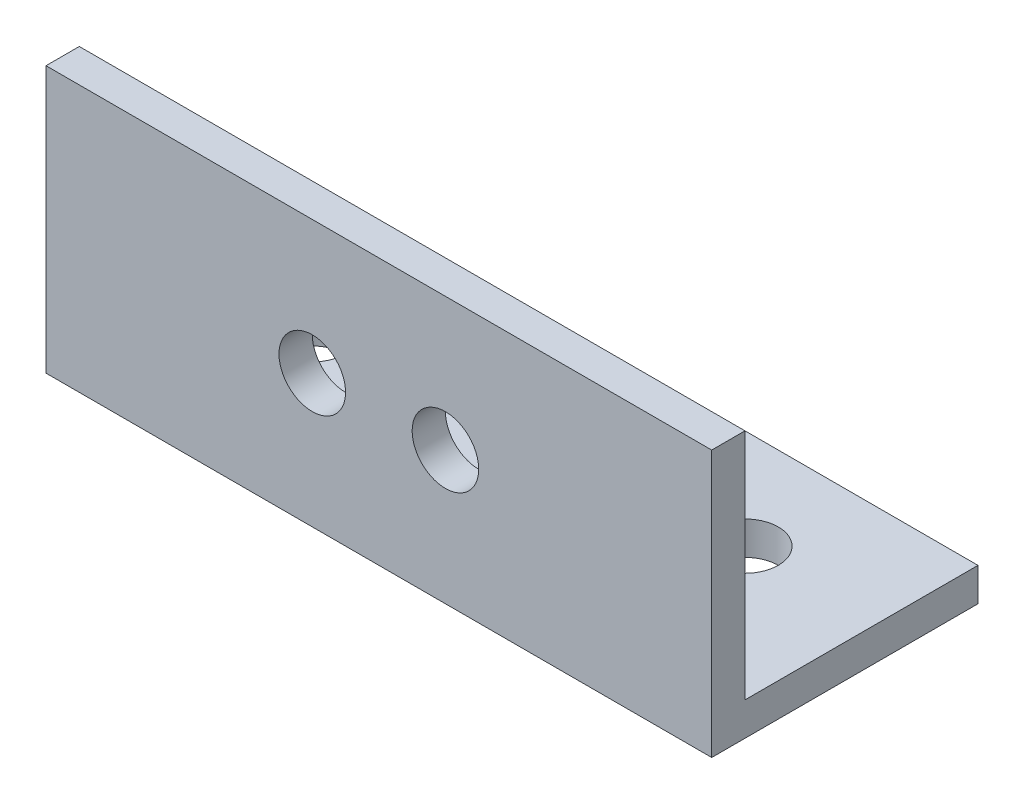
SolidWorks part; units mm, degrees
material "6061-T6 (SS)"
ref_plane "Front Plane" through (0, 0, 0) normal (0, 0, 1) x (1, 0, 0)
ref_plane "Top Plane" through (0, 0, 0) normal (0, 1, 0) x (1, 0, 0)
ref_plane "Right Plane" through (0, 0, 0) normal (1, 0, 0) x (0, 0, -1)
sketch "Sketch1" plane through (0, 0, 0) normal (0, 1, 0) x (1, 0, 0)
  line L1 (-31.75, 12.7) -> (31.75, 12.7)
  line L2 (-31.75, 12.7) -> (-31.75, -12.7)
  line L3 (-31.75, -12.7) -> (31.75, -12.7)
  line L4 (31.75, 12.7) -> (31.75, -12.7)
  line L5 (-31.75, 12.7) -> (31.75, -12.7) construction
  line L6 (-31.75, -12.7) -> (31.75, 12.7) construction
  point P0 (0, 0)
  dimension "D1" = 63.5
  dimension "D2" = 25.4
extrude "Boss-Extrude1" add sketch "Sketch1" along normal blind 3.175
sketch "Sketch2" plane through (0, 3.175, 0) normal (0, 1, 0) x (1, 0, 0)
  line L0 (31.75, -12.7) -> (31.75, 12.7) construction
  line L1 (-31.75, -12.7) -> (31.75, -12.7)
  line L2 (-31.75, -12.7) -> (-31.75, -9.525)
  line L3 (-31.75, -9.525) -> (31.75, -9.525)
  line L4 (31.75, -12.7) -> (31.75, -9.525)
  dimension "D1" = 3.175
extrude "Boss-Extrude2" add sketch "Sketch2" along normal blind 22.225
sketch "Sketch3" plane through (0, 0, 9.525) normal (0, 0, -1) x (-1, 0, 0)
  line L0 (31.75, 25.4) -> (31.75, 3.175) construction
  line L1 (-31.75, 25.4) -> (31.75, 25.4) construction
  line L2 (-31.75, 25.4) -> (-31.75, 3.175) construction
  circle A0 centre (6.35, 12.7) radius 3.175
  circle A1 centre (-6.35, 12.7) radius 3.175
  dimension "D1" = 6.35
  dimension "D2" = 6.35
  dimension "D3" = 25.4
  dimension "D4" = 12.7
  dimension "D5" = 25.4
  dimension "D6" = 12.7
extrude "Cut-Extrude1" cut sketch "Sketch3" against normal blind 3.175
sketch "Sketch4" plane through (0, 3.175, 0) normal (0, 1, 0) x (1, 0, 0)
  line L0 (-31.75, 12.7) -> (-31.75, -9.525) construction
  line L1 (31.75, 12.7) -> (-31.75, 12.7) construction
  line L2 (31.75, -9.525) -> (31.75, 12.7) construction
  line L3 (-31.75, -12.7) -> (31.75, -12.7) construction
  circle A0 centre (-19.05, 0) radius 3.175
  circle A1 centre (19.05, 3.175) radius 3.175
  dimension "D1" = 6.35
  dimension "D2" = 6.35
  dimension "D3" = 12.7
  dimension "D4" = 12.7
  dimension "D5" = 15.875
  dimension "D6" = 12.7
extrude "Cut-Extrude2" cut sketch "Sketch4" against normal blind 3.175
